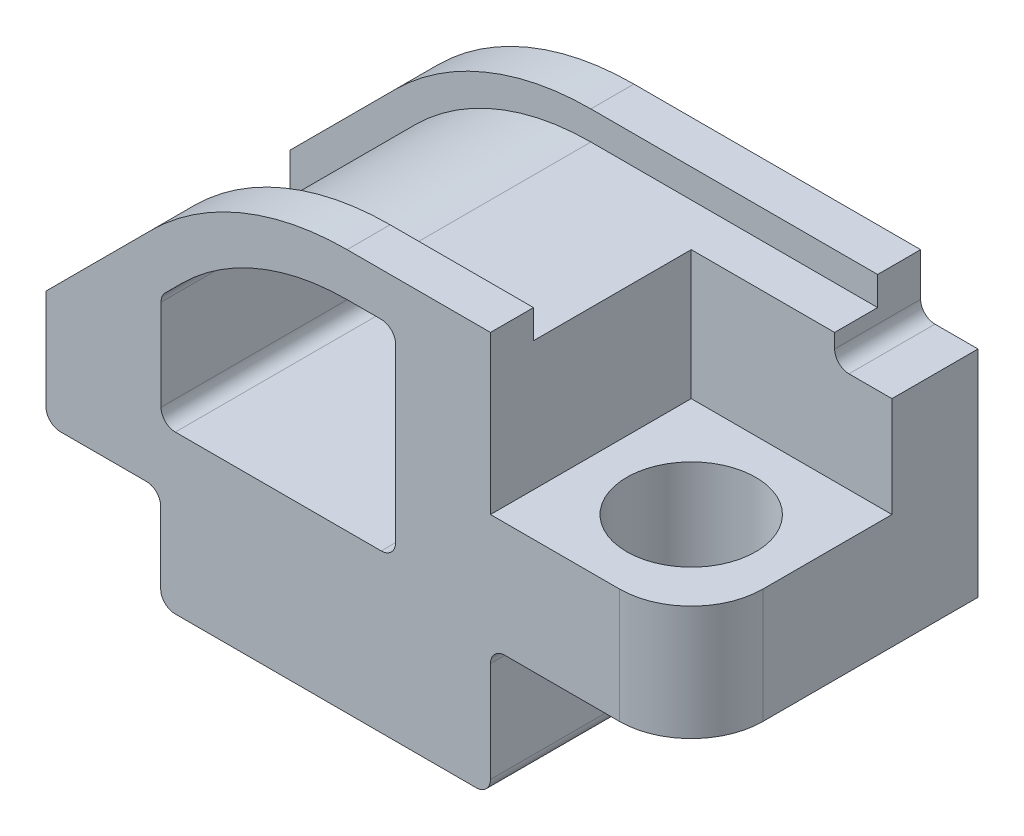
SolidWorks part; units mm, degrees
ref_plane "Front Plane" through (0, 0, 0) normal (0, 0, 1) x (1, 0, 0)
ref_plane "Top Plane" through (0, 0, 0) normal (0, 1, 0) x (1, 0, 0)
ref_plane "Right Plane" through (0, 0, 0) normal (1, 0, 0) x (0, 0, -1)
sketch "Sketch1" plane through (0, 0, 0) normal (0, 0, 1) x (1, 0, 0)
  line L0 (0, 0) -> (1016, 0)
  line L1 (1016, 0) -> (1016, -889)
  line L2 (1016, -889) -> (3937, -889)
  line L3 (3937, -889) -> (3937, 254)
  line L4 (3937, 254) -> (5715, 254)
  line L5 (5715, 254) -> (5715, 2159)
  line L6 (5715, 2159) -> (5207, 2159)
  line L7 (5207, 2159) -> (5207, 2667)
  line L8 (5207, 2667) -> (2667, 2667)
  line L9 (0, 1016) -> (0, 0)
  line L10 (932.5795, 1948.5795) -> (0, 1016)
  arc A2 (2667, 2667) -> (932.5795, 1948.5795) centre (2667, 214.159) ccw
  point P14 (214.159, 1230.159)
  dimension "D1" = 889
  dimension "D2" = 2921
  dimension "D3" = 1143
  dimension "D4" = 1778
  dimension "D5" = 1905
  dimension "D6" = 3556
  dimension "D8" = 2540
  dimension "D9" = 5715
  dimension "D10" = 1016
  dimension "D11" = 45
  dimension "D7" = 508
extrude "Boss-Extrude1" add sketch "Sketch1" along normal mid plane 2540
sketch "Sketch3" plane through (0, 0, 1270) normal (0, 0, 1) x (1, 0, 0)
  line L11 (3096.26, 2283.46) -> (2667, 2283.46)
  line L12 (1203.7832, 1677.3758) -> (1018.54, 1492.1325)
  line L13 (1203.7832, 1677.3758) -> (271.9477, 745.5402) construction
  line L14 (5204.46, 2283.46) -> (2667, 2283.46) construction
  line L15 (1018.54, 1492.1325) -> (1018.54, 506.9479)
  line L16 (1018.54, 506.9479) -> (3096.26, 506.9479)
  line L17 (3096.26, 506.9479) -> (3096.26, 2283.46)
  line L22 (2.54, 1014.9479) -> (2.54, 2.54)
  line L23 (2.54, 2.54) -> (1018.54, 2.54)
  line L24 (1018.54, 2.54) -> (1018.54, -886.46)
  line L25 (1018.54, -886.46) -> (3934.46, -886.46)
  line L26 (3934.46, -886.46) -> (3934.46, 256.54)
  line L27 (3934.46, 256.54) -> (5712.46, 256.54)
  line L28 (5712.46, 256.54) -> (5712.46, 2156.46)
  line L29 (5712.46, 2156.46) -> (5204.46, 2156.46)
  line L30 (5204.46, 2156.46) -> (5204.46, 2664.46)
  line L31 (5204.46, 2664.46) -> (2667, 2664.46)
  line L32 (934.3756, 1946.7835) -> (2.54, 1014.9479)
  line L33 (2.54, 1014.9479) -> (2.54, 2.54)
  line L34 (2.54, 2.54) -> (1018.54, 2.54)
  line L35 (1018.54, 2.54) -> (1018.54, -886.46)
  line L36 (1018.54, -886.46) -> (3934.46, -886.46)
  line L37 (3934.46, -886.46) -> (3934.46, 256.54)
  line L38 (3934.46, 256.54) -> (5712.46, 256.54)
  line L39 (5712.46, 256.54) -> (5712.46, 2156.46)
  line L40 (5712.46, 2156.46) -> (5204.46, 2156.46)
  line L41 (5204.46, 2156.46) -> (5204.46, 2664.46)
  line L42 (5204.46, 2664.46) -> (2667, 2664.46)
  line L43 (934.3756, 1946.7835) -> (2.54, 1014.9479)
  arc A1 (2667, 2283.46) -> (1203.7832, 1677.3758) centre (2667, 214.159) ccw
  arc A2 (2667, 2664.46) -> (934.3756, 1946.7835) centre (2667, 214.159) ccw
  arc A3 (2667, 2664.46) -> (934.3756, 1946.7835) centre (2667, 214.159) ccw
  point P5 (0, 0)
  dimension "D3" = 838.2
  dimension "D4" = 508
  dimension "D1" = 2.54
  dimension "D2" = 381
extrude "Cut-Extrude2" cut sketch "Sketch3" against normal through all contours A1 L12 L15 L16 L17 L11
sketch "Sketch4" plane through (0, 0, 0) normal (0, 0, 1) x (1, 0, 0)
  line L2 (5207, 2159) -> (5207, 2667) construction
  line L3 (5207, 2667) -> (2667, 2667) construction
  line L4 (5207, 2413) -> (2667, 2413)
  line L5 (1112.1846, 1768.9744) -> (179.6051, 836.3949)
  line L6 (5207, 2413) -> (2667, 2413)
  line L7 (1112.1846, 1768.9744) -> (0, 656.7898)
  line L8 (932.5795, 1948.5795) -> (0, 1016) construction
  line L9 (0, 1016) -> (0, 0) construction
  line L10 (5207, 2413) -> (5207, 2667)
  line L11 (5207, 2667) -> (2667, 2667)
  line L12 (932.5795, 1948.5795) -> (0, 1016)
  line L13 (0, 1016) -> (0, 656.7898)
  arc A1 (2667, 2667) -> (932.5795, 1948.5795) centre (2667, 214.159) ccw construction
  arc A2 (2667, 2413) -> (1112.1846, 1768.9744) centre (2667, 214.159) ccw
  arc A3 (2667, 2413) -> (1112.1846, 1768.9744) centre (2667, 214.159) ccw
  arc A4 (2667, 2667) -> (932.5795, 1948.5795) centre (2667, 214.159) ccw
  dimension "D1" = 254
extrude "Cut-Extrude3" cut sketch "Sketch4" against normal mid plane 1778
sketch "Sketch5" plane through (0, 2667, 0) normal (0, 1, 0) x (1, 0, 0)
  line L1 (5715, -1270) -> (3937, -1270)
  line L2 (5715, -1270) -> (5715, 508)
  line L3 (5715, 508) -> (3937, 508)
  line L4 (3937, -1270) -> (3937, 508)
  dimension "D1" = 1778
extrude "Cut-Extrude4" cut sketch "Sketch5" against normal blind 1397
sketch "Sketch6" plane through (0, 1270, 0) normal (0, 1, 0) x (1, 0, 0)
  line L0 (5715, 508) -> (3937, -1270) construction
  circle A0 centre (4826, -381) radius 571.5
  dimension "D1" = 1143
extrude "Cut-Extrude5" cut sketch "Sketch6" against normal through all
fillet "Fillet1" radius 635 1 edges at (5715, 762, 1270)
fillet "Fillet2" radius 127 6 edges at (5207, 2159, -889) (3937, 254, 0) (3937, -889, 0) (1016, -889, 0) (1016, 0, 0) (0, 0, 0)
fillet "Fillet3" radius 127 4 edges at (3096.26, 506.9479, 0) (3096.26, 2283.46, 0) (1018.54, 1492.1325, 0) (1018.54, 506.9479, 0)
equation "\"D\"= 45"
equation "\"A\"=225"
equation "\"B\"= 40"
equation "\"C\"= 45"
equation "\"D9@Sketch1\"=\"A\""
equation "\"D10@Sketch1\"=\"B\""
equation "\"D1@Sketch6\"=\"C\""
